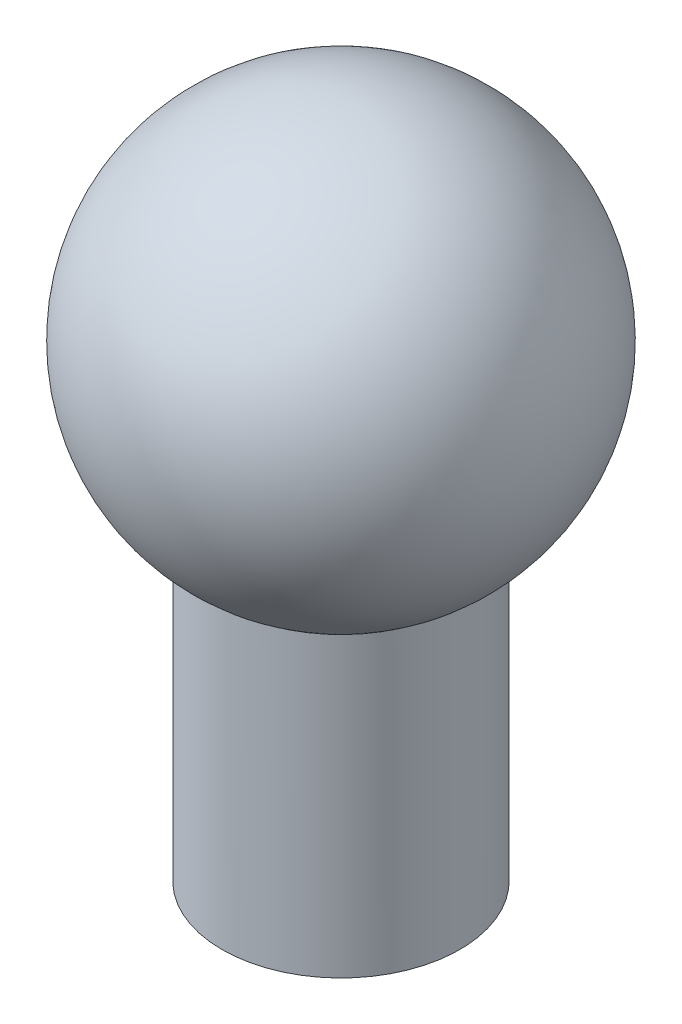
SolidWorks part; units mm, degrees
ref_plane "前视基准面" through (0, 0, 0) normal (0, 0, 1) x (1, 0, 0)
ref_plane "上视基准面" through (0, 0, 0) normal (0, 1, 0) x (1, 0, 0)
ref_plane "右视基准面" through (0, 0, 0) normal (1, 0, 0) x (0, 0, -1)
sketch "草图1" plane through (0, 0, 0) normal (0, 0, 1) x (1, 0, 0)
  line L0 (0, 0) -> (4, 0)
  line L1 (4, 0) -> (4, 10)
  line L2 (0, 0) -> (0, 22.7446)
  arc A0 (0, 22.7446) -> (4, 10) centre (0, 15.7446) cw
  point P7 (0, 0)
  dimension "D1" = 7
  dimension "D2" = 4
  dimension "D3" = 10
revolve "旋转1" add sketch "草图1" angle 360 about L2
